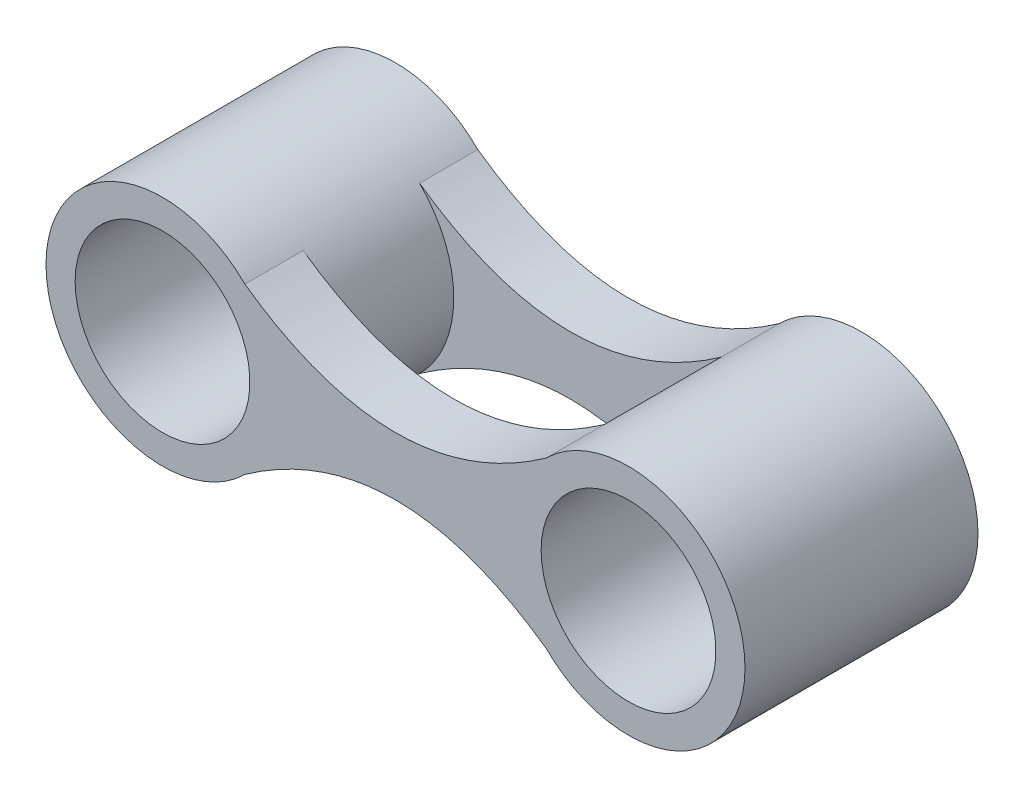
SolidWorks part; units mm, degrees
ref_plane "Front Plane" through (0, 0, 0) normal (0, 0, 1) x (1, 0, 0)
ref_plane "Top Plane" through (0, 0, 0) normal (0, 1, 0) x (1, 0, 0)
ref_plane "Right Plane" through (0, 0, 0) normal (1, 0, 0) x (0, 0, -1)
sketch "Sketch1" plane through (0, 0, 0) normal (0, 0, 1) x (1, 0, 0)
  line L0 (-6.35, 0) -> (6.35, 0) construction
  line L1 (-6.35, 0) -> (-6.35, 5.3941) construction
  line L2 (0, -9.5021) -> (0, 10.9777) construction
  line L3 (-6.35, 0) -> (0, 6.35) construction
  line L4 (0, 6.35) -> (6.35, 0) construction
  line L5 (-2.1004, 0.7937) -> (1.9982, 0.7937) construction
  arc A0 (-4.1049, 2.2451) -> (-4.1049, -2.2451) centre (-6.35, 0) ccw
  arc A1 (4.1049, -2.2451) -> (4.1049, 2.2451) centre (6.35, 0) ccw
  spline S0 degree 2 poles (-4.1049, 2.2451) (0, -0.6576) (4.1049, 2.2451) knots 0 0 0 1 1 1
  spline S1 degree 2 poles (-4.1049, -2.2451) (0, 0.6576) (4.1049, -2.2451) knots 0 0 0 1 1 1
  point P7 (-4.1049, 2.2451)
  point P12 (4.1049, 2.2451)
  dimension "D1" = 6.35
  dimension "D2" = 6.35
  dimension "D3" = 12.7
  dimension "D4" = 0.7937
extrude "Boss-Extrude1" add sketch "Sketch1" along normal blind 1.5875
ref_plane "chainplane" through (0, 0, 3.175) normal (0, 0, 1) x (1, 0, 0)
sketch "Sketch2" plane through (0, 0, 1.5875) normal (0, 0, 1) x (1, 0, 0)
  circle A0 centre (-6.35, 0) radius 3.175
  circle A1 centre (6.35, 0) radius 3.175
extrude "Boss-Extrude2" add sketch "Sketch2" along normal blind 3.175
mirror "Mirror1" about plane through (0, 0, 3.175) normal (0, 0, 1) of "Boss-Extrude1"
sketch "Sketch3" plane through (0, 0, 0) normal (0, 0, -1) x (-1, 0, 0)
  circle A0 centre (-6.35, 0) radius 2.3813
  circle A1 centre (6.35, 0) radius 2.3813
  dimension "D1" = 4.7625
  dimension "D2" = 4.7625
extrude "Cut-Extrude1" cut sketch "Sketch3" against normal blind 6.35
scale "Scale1" scale about centroid uniform scaling yes scale factor 0.75
equation "\"large_diameter\" = 1/4in"
equation "\"small_diameter\" = 1/8in"
equation "\"arc_height\" = 1/32in"
equation "\"chain_space\" = 1/2in"
equation "\"chain_thickness\" = 1/16in"
equation "\"outer_height\" = 3/16in"
equation "\"inner_height\" = 2/16in"
equation "\"D1@Sketch1\" = \"large_diameter\""
equation "\"D2@Sketch1\" = \"large_diameter\""
equation "\"D3@Sketch1\"= \"chain_space\""
equation "\"D4@Sketch1\"= \"arc_height\""
equation "\"D1@Boss-Extrude1\"=\"chain_thickness\"\""
equation "\"D1@chainplane\" = \"inner_height\" / 2"
equation "\"D1@Boss-Extrude2\"= \"inner_height\""
equation "\"D1@Sketch3\" = \"small_diameter\" + \"give\""
equation "\"D2@Sketch3\" = \"small_diameter\" + \"give\""
equation "\"D1@Cut-Extrude1\"=\"inner_height\"*2"
equation "\"give\" = 1/16in"
